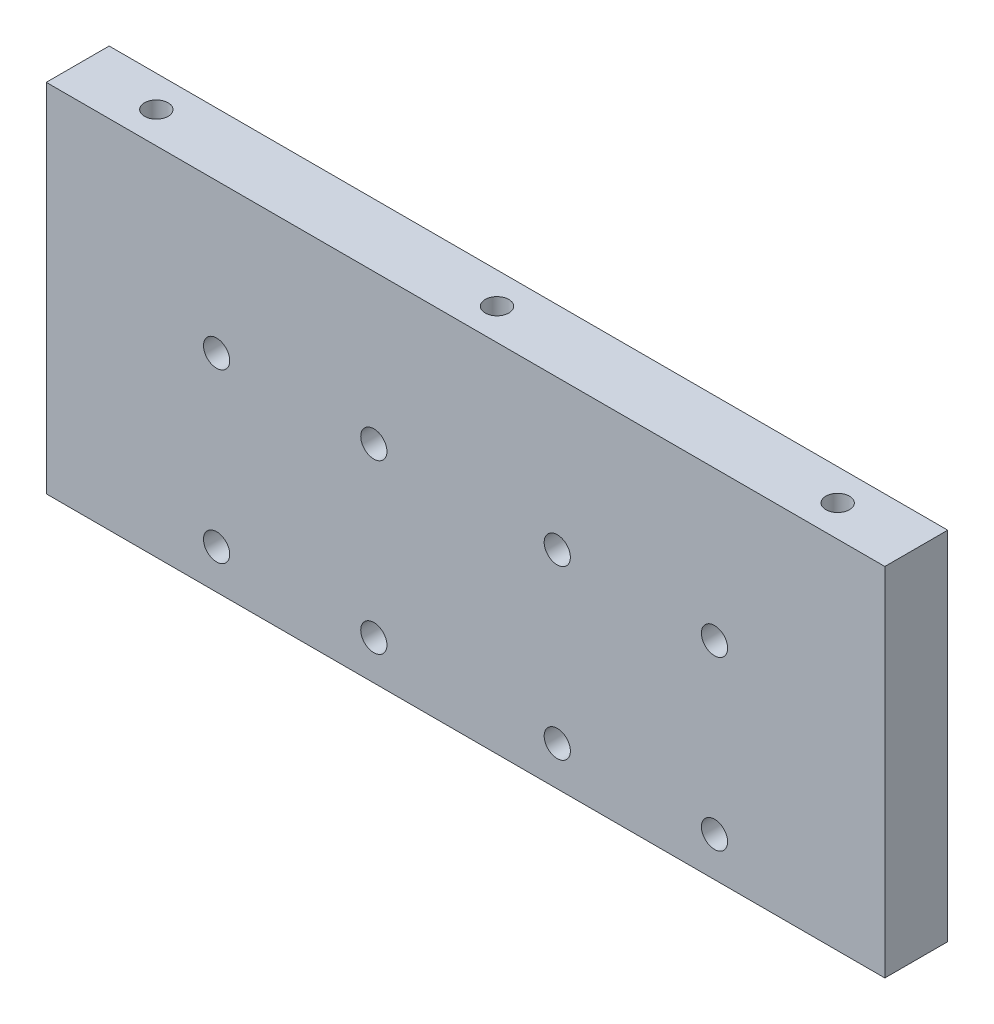
SolidWorks part; units mm, degrees
ref_plane "Plan de face" through (0, 0, 0) normal (0, 0, 1) x (1, 0, 0)
ref_plane "Plan de dessus" through (0, 0, 0) normal (0, 1, 0) x (1, 0, 0)
ref_plane "Plan de droite" through (0, 0, 0) normal (1, 0, 0) x (0, 0, -1)
sketch "Esquisse1" plane through (0, 0, 0) normal (0, 0, 1) x (1, 0, 0)
  line L0 (80, 68) -> (80, -12.9482) construction
  line L1 (0, 0) -> (160, 0)
  line L2 (0, 0) -> (0, 68)
  line L3 (0, 68) -> (160, 68)
  line L4 (160, 0) -> (160, 68)
  line L5 (80, 39.5) -> (36.7873, 39.5) construction
  circle A0 centre (62.5, 39.5) radius 2.5
  circle A1 centre (32.5, 39.5) radius 2.5
  circle A2 centre (32.5, 7.5) radius 2.5
  circle A3 centre (62.5, 7.5) radius 2.5
  circle A4 centre (97.5, 7.5) radius 2.5
  circle A5 centre (127.5, 7.5) radius 2.5
  circle A6 centre (127.5, 39.5) radius 2.5
  circle A7 centre (97.5, 39.5) radius 2.5
  dimension "D3" = 5
  dimension "D5" = 17.5
  dimension "D1" = 160
  dimension "D2" = 68
  dimension "D4" = 39.5
  dimension "D6" = 2
  dimension "D7" = 2
extrude "Boss.-Extru.1" add sketch "Esquisse1" along normal blind 12
sketch "Esquisse2" plane through (0, 68, 0) normal (0, 1, 0) x (1, 0, 0)
  line L0 (0, -6) -> (160, -6) construction
  line L1 (0, -12) -> (0, 0) construction
  line L2 (160, -12) -> (160, 0) construction
  circle A0 centre (15, -6) radius 2.25
  circle A1 centre (80, -6) radius 2.25
  circle A2 centre (145, -6) radius 2.25
  dimension "D1" = 4.5
  dimension "D2" = 15
  dimension "D3" = 3
extrude "Enlèv. mat.-Extru.1" cut sketch "Esquisse2" against normal blind 15
sketch "Esquisse3" plane through (0, 0, 0) normal (0, 0, -1) x (-1, 0, 0)
  circle A0 centre (-127.5, 39.5) radius 4.5
  circle A1 centre (-127.5, 7.5) radius 4.5
  circle A2 centre (-97.5, 39.5) radius 4.5
  circle A3 centre (-62.5, 39.5) radius 4.5
  circle A4 centre (-97.5, 7.5) radius 4.5
  circle A5 centre (-62.5, 7.5) radius 4.5
  circle A6 centre (-32.5, 7.5) radius 4.5
  circle A7 centre (-32.5, 39.5) radius 4.5
  dimension "D1" = 9
extrude "Enlèv. mat.-Extru.2" cut sketch "Esquisse3" against normal blind 5
